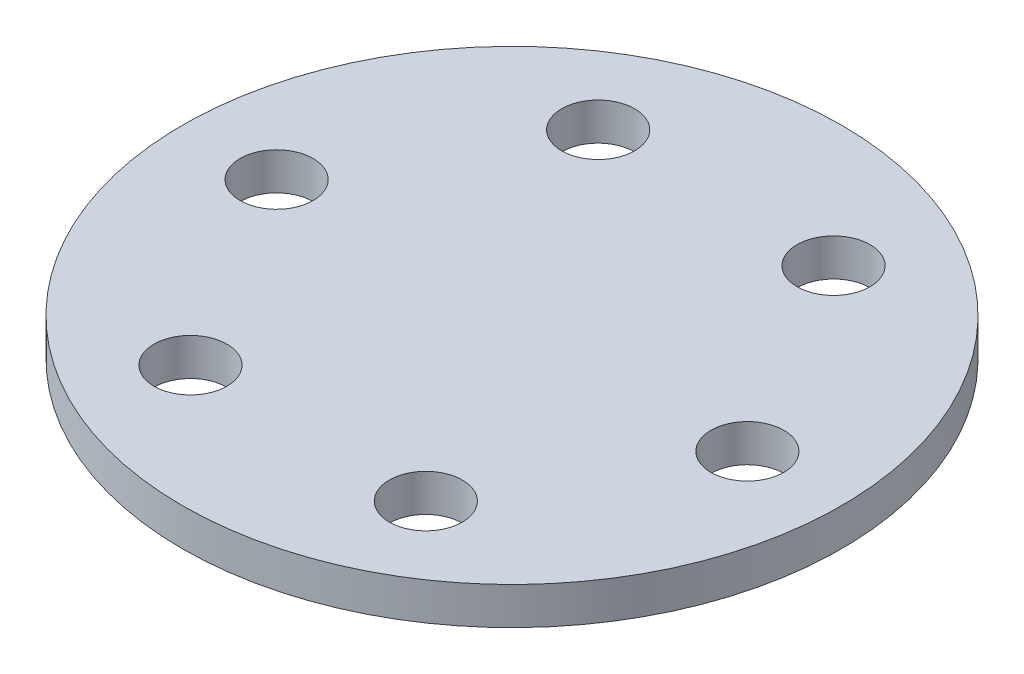
SolidWorks part; units mm, degrees
ref_plane "Front" through (0, 0, 0) normal (0, 0, 1) x (1, 0, 0)
ref_plane "Top" through (0, 0, 0) normal (0, 1, 0) x (1, 0, 0)
ref_plane "Right" through (0, 0, 0) normal (1, 0, 0) x (0, 0, -1)
sketch "Sketch1" plane through (0, 0, 0) normal (0, 1, 0) x (1, 0, 0)
  circle A0 centre (0, 0) radius 14
  dimension "D1" = 28
extrude "Boss-Extrude1" add sketch "Sketch1" along normal blind 1.5875
sketch "Sketch2" plane through (0, 1.5875, 0) normal (0, 1, 0) x (1, 0, 0)
  circle A0 centre (0, 0) radius 10
  point P3 (-10, 0)
  point P5 (-5, 8.6603)
  point P8 (5, 8.6603)
  point P9 (10, 0)
  point P10 (5, -8.6603)
  point P11 (-5, -8.6603)
  point P12 (0, 0)
  dimension "D1" = 20
  dimension "D2" = 6
hole_wizard "Ø3.0mm Dowel Hole1" positions "Sketch3" profile "Sketch4" hole size "Ø3.0" standard "ISO" end condition through all
sketch "Sketch3" plane through (0, 1.5875, 0) normal (0, 1, 0) x (1, 0, 0)
  point P0 (-5, -8.6603)
  point P3 (-10, 0)
  point P6 (-5, 8.6603)
  point P9 (5, 8.6603)
  point P12 (10, 0)
  point P15 (5, -8.6603)
sketch "Sketch4" plane through (-5, 1.5875, 8.6603) normal (1, 0, 0) x (0, 0, 1)
  line L0 (0, 0) -> (0, 1.5875)
  line L1 (0, 1.5875) -> (1.55, 1.5875)
  line L2 (1.55, 1.5875) -> (1.55, 0)
  line L5 (1.55, 0) -> (0, 0)
  line L11 (0, -6.35) -> (0, 107.95) construction
  dimension "Thru Hole Dia." = 3.1
  dimension "Thru Hole Depth" = 1.5875
